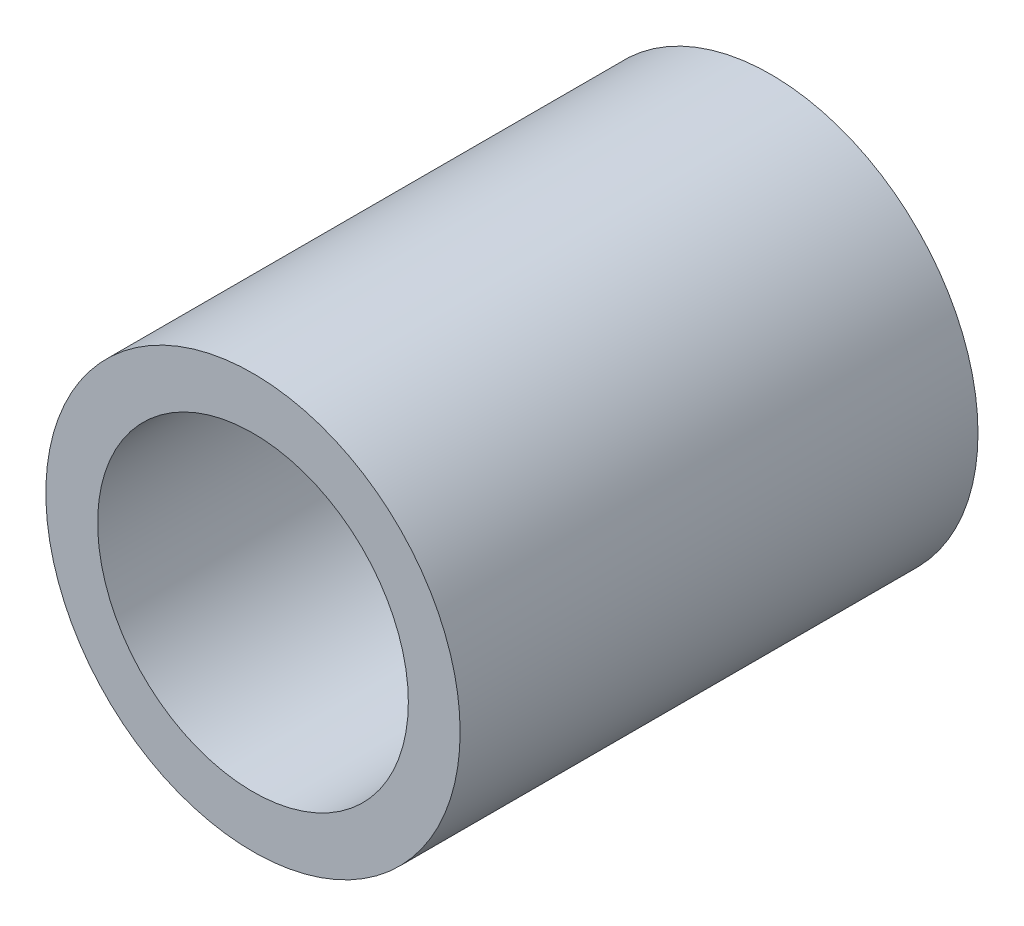
SolidWorks part; units mm, degrees
ref_plane "Plan de face" through (0, 0, 0) normal (0, 0, 1) x (1, 0, 0)
ref_plane "Plan de dessus" through (0, 0, 0) normal (0, 1, 0) x (1, 0, 0)
ref_plane "Plan de droite" through (0, 0, 0) normal (1, 0, 0) x (0, 0, -1)
sketch "Esquisse1" plane through (0, 0, 0) normal (0, 0, 1) x (1, 0, 0)
  circle A0 centre (0, 0) radius 1.5
  circle A1 centre (0, 0) radius 2
  dimension "D1" = 3
  dimension "D2" = 4
extrude "Boss.-Extru.1" add sketch "Esquisse1" along normal blind 5
